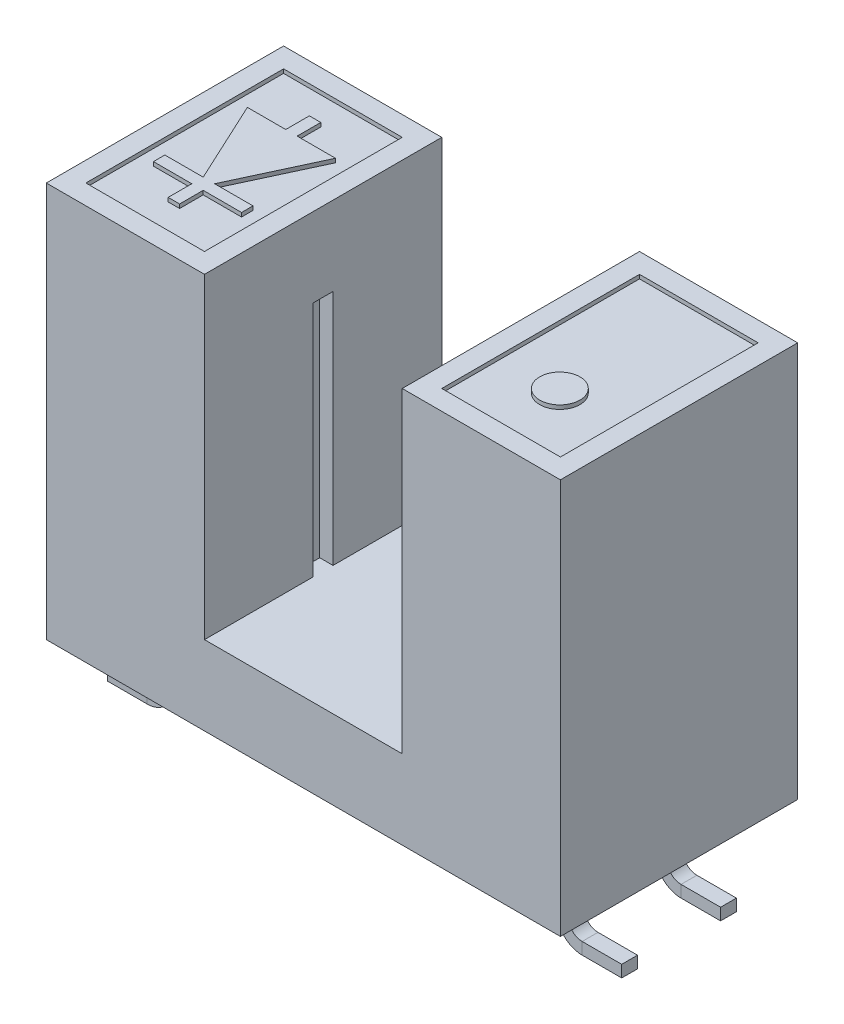
SolidWorks part; units mm, degrees
ref_plane "Front Plane" through (0, 0, 0) normal (0, 0, 1) x (1, 0, 0)
ref_plane "Top Plane" through (0, 0, 0) normal (0, 1, 0) x (1, 0, 0)
ref_plane "Right Plane" through (0, 0, 0) normal (1, 0, 0) x (0, 0, -1)
sketch "Sketch1" plane through (0, 0, 0) normal (0, 0, 1) x (1, 0, 0)
  line L0 (6.5, 0) -> (-6.5, 0)
  line L1 (-6.5, 0) -> (-6.5, 10)
  line L2 (-6.5, 10) -> (-2.5, 10)
  line L3 (-2.5, 10) -> (-2.5, 2)
  line L4 (-2.5, 2) -> (2.5, 2)
  line L5 (2.5, 2) -> (2.5, 10)
  line L6 (2.5, 10) -> (6.5, 10)
  line L7 (6.5, 10) -> (6.5, 0)
  point P6 (0, 0)
  point P10 (0, 2)
  dimension "D1" = 13
  dimension "D2" = 10
  dimension "D3" = 2
  dimension "D4" = 5
extrude "Base" add sketch "Sketch1" along normal mid plane 6
sketch "Sketch2" plane through (0, 10, 0) normal (0, 1, 0) x (1, 0, 0)
  line L19 (-4.6444, 1.1983) -> (-5.6141, 1.1983)
  line L21 (-4.6444, -0.8881) -> (-5.6141, -0.8881)
  line L22 (-5.6141, -0.8881) -> (-5.6141, -1.1769)
  line L23 (-6, 2.5) -> (-6, -2.5)
  line L24 (-6, -2.5) -> (-3, -2.5)
  line L25 (-3, -2.5) -> (-3, 2.5)
  line L26 (-3, 2.5) -> (-6, 2.5)
  line L27 (-6, 2.5) -> (-6, -2.5)
  line L28 (-6, -2.5) -> (-3, -2.5)
  line L29 (-3, -2.5) -> (-3, 2.5)
  line L30 (-3, 2.5) -> (-6, 2.5)
  line L31 (-5.6141, -1.1769) -> (-4.6444, -1.1769)
  line L32 (-4.6444, -1.1769) -> (-4.6444, -1.7738)
  line L33 (-4.6444, -1.7738) -> (-4.3556, -1.7738)
  line L34 (-4.3556, -1.7738) -> (-4.3556, -1.1769)
  line L35 (-4.3556, -1.1769) -> (-3.3859, -1.1769)
  line L36 (-3.3859, -1.1769) -> (-3.3859, -0.8881)
  line L37 (-3.3859, -0.8881) -> (-4.3556, -0.8881)
  line L39 (-3.3859, 1.1983) -> (-4.3556, 1.1983)
  line L40 (-4.3556, 1.1983) -> (-4.3556, 1.7965)
  line L41 (-4.3556, 1.7965) -> (-4.6444, 1.7965)
  line L42 (-4.6444, 1.7965) -> (-4.6444, 1.1983)
  line L43 (-5.6141, 1.1983) -> (-4.6444, -0.8881)
  line L44 (-3.3859, 1.1983) -> (-4.3556, -0.8881)
  line L45 (-4.5, -2.5) -> (-4.5, 2.5) construction
  line L60 (3, -2.5) -> (6, -2.5)
  line L61 (3, 2.5) -> (3, -2.5)
  line L62 (6, -2.5) -> (6, 2.5)
  line L63 (6, 2.5) -> (3, 2.5)
  line L64 (3, -2.5) -> (6, -2.5)
  line L65 (3, 2.5) -> (3, -2.5)
  line L66 (6, -2.5) -> (6, 2.5)
  line L67 (6, 2.5) -> (3, 2.5)
  circle A0 centre (4.4921, -1.0069) radius 0.5091
  point P18 (-4.5, -1.7738)
  dimension "D2" = 0.5
  dimension "D1" = 0.5
extrude "Polarity" cut sketch "Sketch2" against normal blind 0.1
sketch "Sketch3" plane through (0, 2, 0) normal (0, 1, 0) x (1, 0, 0)
  line L0 (-2.5, -3) -> (-2.5, 3) construction
  line L1 (-2.1644, -0.25) -> (-2.8356, -0.25)
  line L2 (-2.1644, -0.25) -> (-2.1644, 0.25)
  line L3 (-2.1644, 0.25) -> (-2.8356, 0.25)
  line L4 (-2.8356, -0.25) -> (-2.8356, 0.25)
  line L5 (-2.1644, -0.25) -> (-2.8356, 0.25) construction
  line L6 (-2.1644, 0.25) -> (-2.8356, -0.25) construction
  line L7 (2.5, -3) -> (2.5, 3) construction
  line L8 (2.7983, -0.25) -> (2.2017, -0.25)
  line L9 (2.7983, -0.25) -> (2.7983, 0.25)
  line L10 (2.7983, 0.25) -> (2.2017, 0.25)
  line L11 (2.2017, -0.25) -> (2.2017, 0.25)
  line L12 (2.7983, -0.25) -> (2.2017, 0.25) construction
  line L13 (2.7983, 0.25) -> (2.2017, -0.25) construction
  point P0 (-2.5, 0)
  point P7 (2.5, 0)
  dimension "D1" = 0.5
extrude "LightSlot" cut sketch "Sketch3" along normal blind 6
sketch "Sketch4" plane through (0, 0, 0) normal (0, -1, 0) x (1, 0, 0)
  line L0 (-1.3732, 0) -> (0, 0) construction
  line L1 (-5.15, 1.45) -> (-4.85, 1.45) construction
  line L2 (-5.15, 1.45) -> (-5.15, 1.05) construction
  line L3 (-5.15, 1.05) -> (-4.85, 1.05) construction
  line L4 (-4.85, 1.45) -> (-4.85, 1.05) construction
  line L5 (-5.15, 1.45) -> (-4.85, 1.05) construction
  line L6 (-5.15, 1.05) -> (-4.85, 1.45) construction
  line L7 (-5.15, -1.05) -> (-4.85, -1.05) construction
  line L8 (-5.15, -1.05) -> (-5.15, -1.45) construction
  line L9 (-5.15, -1.45) -> (-4.85, -1.45) construction
  line L10 (-4.85, -1.05) -> (-4.85, -1.45) construction
  line L11 (-5.15, -1.05) -> (-4.85, -1.45) construction
  line L12 (-5.15, -1.45) -> (-4.85, -1.05) construction
  line L13 (4.85, 1.45) -> (5.15, 1.45)
  line L14 (4.85, 1.45) -> (4.85, 1.05)
  line L15 (4.85, 1.05) -> (5.15, 1.05)
  line L16 (5.15, 1.45) -> (5.15, 1.05)
  line L17 (4.85, 1.45) -> (5.15, 1.05) construction
  line L18 (4.85, 1.05) -> (5.15, 1.45) construction
  line L19 (4.85, -1.05) -> (5.15, -1.05)
  line L20 (4.85, -1.05) -> (4.85, -1.45)
  line L21 (4.85, -1.45) -> (5.15, -1.45)
  line L22 (5.15, -1.05) -> (5.15, -1.45)
  line L23 (4.85, -1.05) -> (5.15, -1.45) construction
  line L24 (4.85, -1.45) -> (5.15, -1.05) construction
  line L25 (0, 0) -> (0, 1.4342) construction
  point P0 (-5, 1.25)
  point P5 (-5, -1.25)
  point P10 (5, 1.25)
  point P15 (5, -1.25)
  dimension "D1" = 0.4
  dimension "D2" = 0.3
  dimension "D3" = 2.5
  dimension "D4" = 10
sketch3d "3DSketch1"
  line L0 (5, 0, 1.25) -> (5, -1.0345, 1.25)
  line L1 (5.5, -1.5345, 1.25) -> (6.5, -1.5345, 1.25)
  arc A0 (5, -1.0345, 1.25) -> (5.5, -1.5345, 1.25) centre (5.5, -1.0345, 1.25) ccw
  point P3 (0, 0, 0)
  point P7 (5, -1.5345, 1.25)
  point P8 (5.5, -1.0345, 1.75)
  point P9 (0, 0, 0)
  dimension "D1" = 0.5
sweep "Sweep1" add profiles "Sketch4" path "3DSketch1"
mirror "Mirror1" about plane through (0, 0, 0) normal (1, 0, 0) of "Sweep1"
